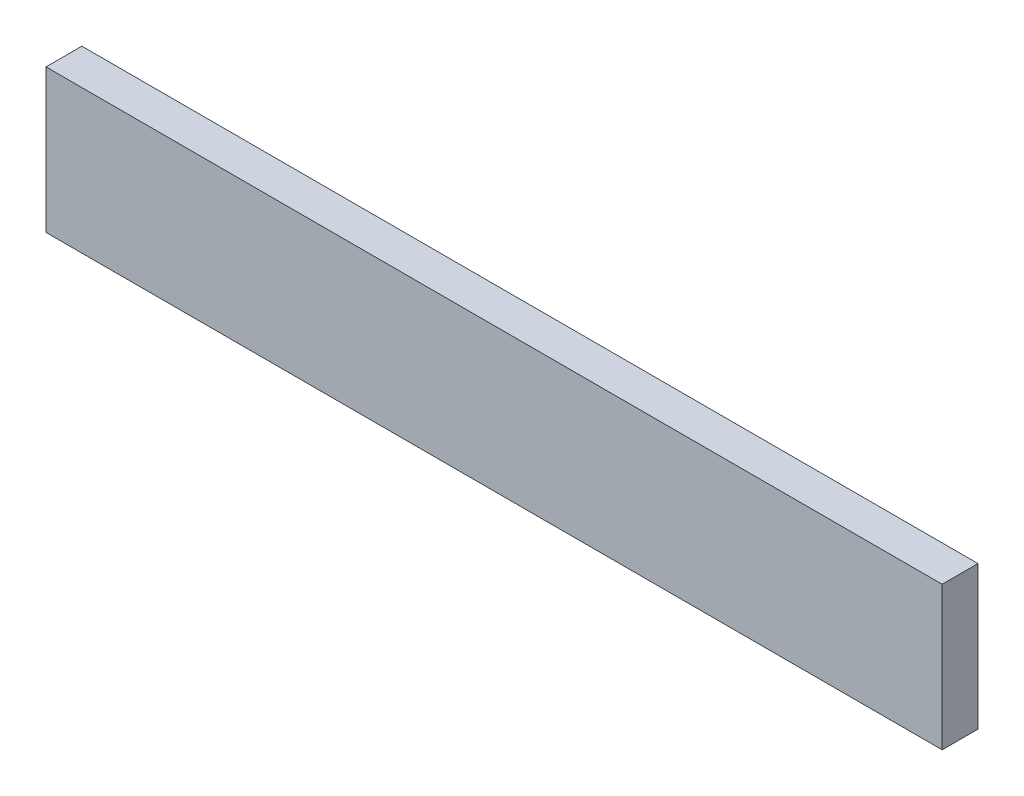
SolidWorks part; units mm, degrees
material "AISI 304"
ref_plane "Front Plane" through (0, 0, 0) normal (0, 0, 1) x (1, 0, 0)
ref_plane "Top Plane" through (0, 0, 0) normal (0, 1, 0) x (1, 0, 0)
ref_plane "Right Plane" through (0, 0, 0) normal (1, 0, 0) x (0, 0, -1)
sketch "Sketch1" plane through (0, 0, 0) normal (0, 0, 1) x (1, 0, 0)
  line L1 (0, 0) -> (50, 0)
  line L2 (0, 0) -> (0, -8)
  line L3 (0, -8) -> (50, -8)
  line L4 (50, 0) -> (50, -8)
  dimension "D1" = 8
  dimension "D2" = 50
extrude "Boss-Extrude1" add sketch "Sketch1" along normal blind 2
